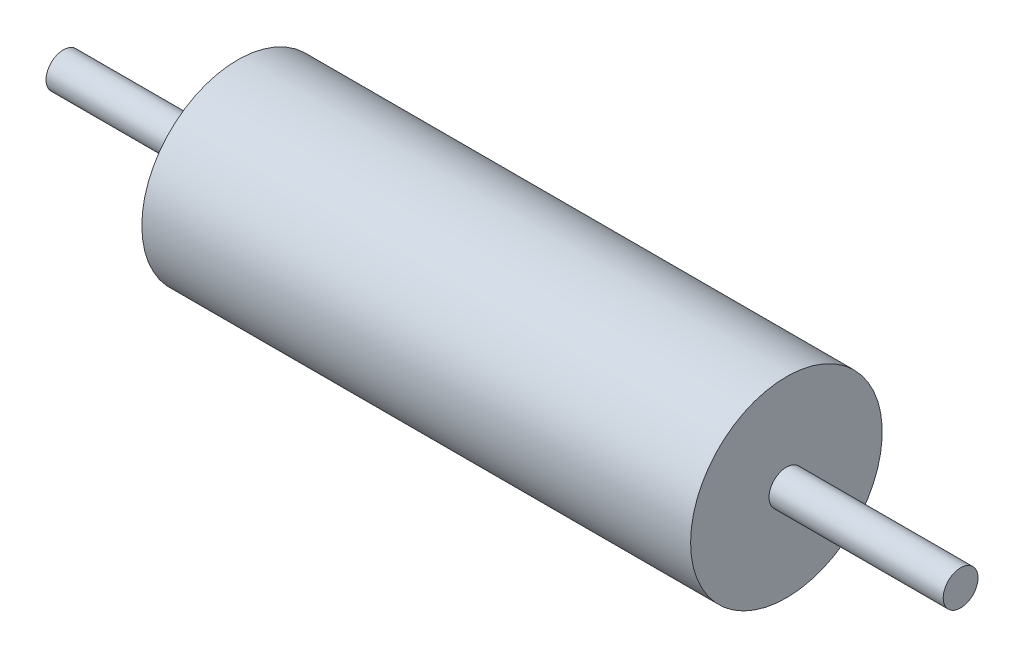
SolidWorks part; units mm, degrees
ref_plane "Спереди" through (0, 0, 0) normal (0, 0, 1) x (1, 0, 0)
ref_plane "Сверху" through (0, 0, 0) normal (0, 1, 0) x (1, 0, 0)
ref_plane "Справа" through (0, 0, 0) normal (1, 0, 0) x (0, 0, -1)
sketch "Эскиз1" plane through (0, 0, 0) normal (0, 1, 0) x (1, 0, 0)
  line L0 (0, 0) -> (-6.3, 0)
  line L1 (0, 0) -> (0, 1.1) construction
  line L2 (0, 1.1) -> (-6.3, 1.1)
  line L3 (-6.3, 1.1) -> (-6.3, 0) construction
  line L4 (0, 0) -> (2.179, 0) construction
  line L5 (-6.3, 1.1) -> (-6.3, 0.2)
  line L6 (-6.3, 0.2) -> (-8.3, 0.2)
  line L7 (-8.3, 0.2) -> (-8.3, 0)
  line L8 (-8.3, 0) -> (-6.3, 0)
  line L9 (0, 1.1) -> (0, 0.2)
  line L10 (0, 0.2) -> (2, 0.2)
  line L11 (2, 0.2) -> (2, 0)
  line L12 (0, 0) -> (2, 0)
  dimension "D1" = 2.2
  dimension "D2" = 6.3
  dimension "D3" = 0.4
  dimension "D4" = 2
revolve "Повернуть1" add sketch "Эскиз1" angle 360 about L4
